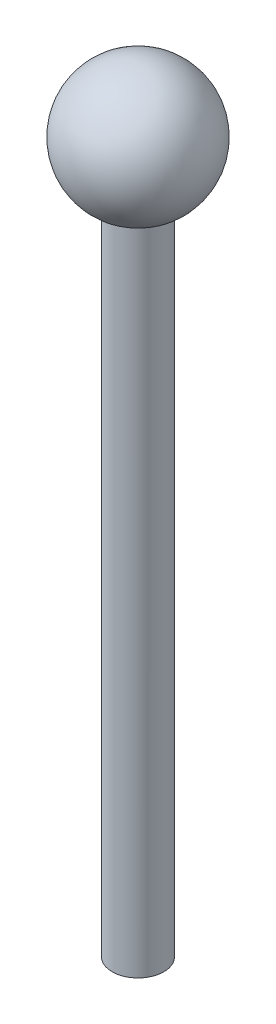
SolidWorks part; units mm, degrees
ref_plane "Front Plane" through (0, 0, 0) normal (0, 0, 1) x (1, 0, 0)
ref_plane "Top Plane" through (0, 0, 0) normal (0, 1, 0) x (1, 0, 0)
ref_plane "Right Plane" through (0, 0, 0) normal (1, 0, 0) x (0, 0, -1)
sketch "Sketch1" plane through (0, 0, 0) normal (0, 0, 1) x (1, 0, 0)
  line L0 (0, 0) -> (-2, 0)
  line L1 (-2, 0) -> (-2, 50.4174)
  line L16 (0, 0) -> (0, 60)
  arc A0 (0, 60) -> (-2, 50.4174) centre (0, 55) ccw
  dimension "D1" = 10
  dimension "D2" = 60
  dimension "D3" = 2
revolve "Revolve1" add sketch "Sketch1" angle 360 about L16
sketch "Sketch3" plane through (0, 100, 0) normal (0, 1, 0) x (1, 0, 0)
  circle A0 centre (0, 0) radius 31
  circle A1 centre (0, 0) radius 31 construction
